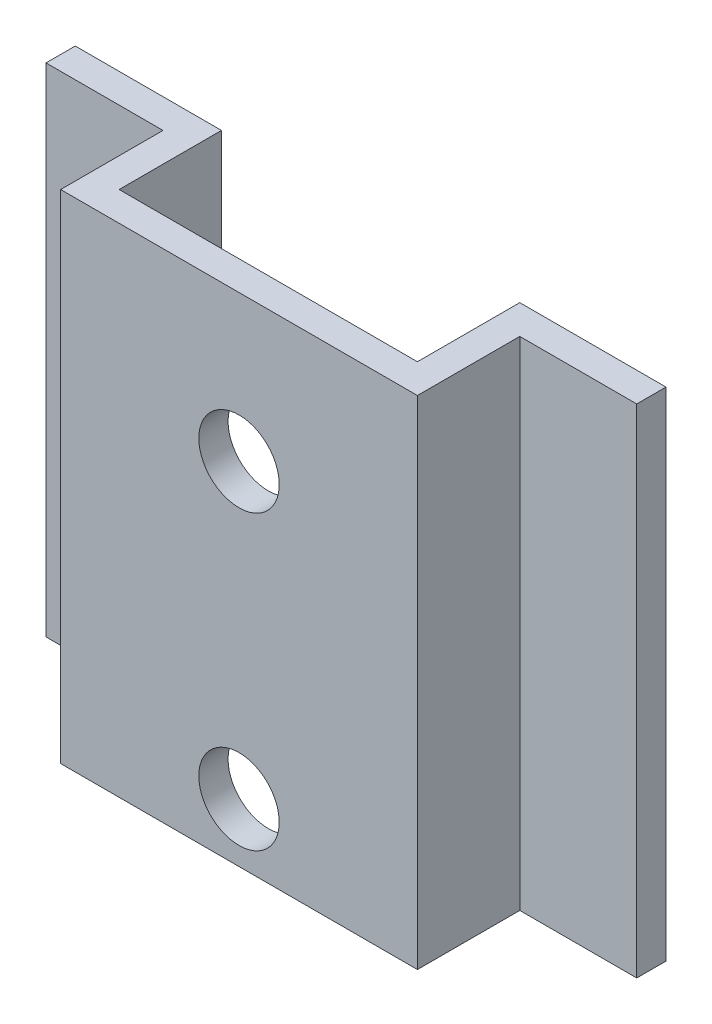
SolidWorks part; units mm, degrees
ref_plane "Front Plane" through (0, 0, 0) normal (0, 0, 1) x (1, 0, 0)
ref_plane "Top Plane" through (0, 0, 0) normal (0, 1, 0) x (1, 0, 0)
ref_plane "Right Plane" through (0, 0, 0) normal (1, 0, 0) x (0, 0, -1)
sketch "Sketch1" plane through (0, 0, 0) normal (0, 0, 1) x (1, 0, 0)
  line L1 (-10, 28) -> (10, 28)
  line L4 (-10, 27) -> (10, 27)
  line L5 (10, 27) -> (10, 62)
  line L6 (10, 62) -> (-10, 62)
  line L7 (-10, 62) -> (-10, 27)
  line L9 (10, 28) -> (10, 62)
  line L10 (10, 62) -> (-10, 62)
  line L11 (-10, 62) -> (-10, 28)
  circle A0 centre (0, 32) radius 2.75 construction
  circle A1 centre (0, 52) radius 2.75 construction
  circle A2 centre (0, 32) radius 2.75
  circle A3 centre (0, 52) radius 2.75
  dimension "D2" = 1
  dimension "D1" = 0
extrude "Boss-Extrude1" add sketch "Sketch1" along normal blind 2
sketch "Sketch2" plane through (0, 0, 0) normal (0, 0, -1) x (-1, 0, 0)
  line L0 (10, 62) -> (10.2, 62)
  line L1 (-10, 62) -> (-10.2, 62)
  line L2 (-10.2, 62) -> (-10.2, 28)
  line L3 (-10, 28) -> (-10.2, 28)
  line L4 (-10, 28) -> (-10, 62) construction
  line L5 (-10, 28) -> (-10, 62)
  line L6 (10.2, 62) -> (10.2, 28)
  line L7 (10, 28) -> (10.2, 28)
  line L8 (10, 62) -> (10, 28) construction
  line L9 (10, 62) -> (10, 28)
  line L11 (10.2, 62) -> (20.2, 62)
  line L12 (10.2, 62) -> (10.2, 28)
  line L13 (10.2, 28) -> (20.2, 28)
  line L14 (20.2, 62) -> (20.2, 28)
  line L15 (-10.2, 62) -> (-20.2, 62)
  line L16 (-10.2, 62) -> (-10.2, 28)
  line L17 (-10.2, 28) -> (-20.2, 28)
  line L18 (-20.2, 62) -> (-20.2, 28)
  dimension "D1" = 0.2
  dimension "D2" = 0.2
  dimension "D3" = 10
  dimension "D4" = 10
extrude "Boss-Extrude2" add sketch "Sketch2" against normal blind 2 separate body contours L14 L11 L6 L13 | L15 L18 L17 L2
sketch "Sketch3" plane through (0, 0, 0) normal (0, 0, -1) x (-1, 0, 0)
  line L4 (-10.2, 62) -> (-20.2, 62)
  line L5 (-20.2, 62) -> (-20.2, 28)
  line L6 (-20.2, 28) -> (-10.2, 28)
  line L7 (-10.2, 28) -> (-10.2, 62)
  line L8 (-10.2, 62) -> (-20.2, 62)
  line L9 (-20.2, 62) -> (-20.2, 28)
  line L10 (-20.2, 28) -> (-10.2, 28)
  line L11 (-10.2, 28) -> (-10.2, 62)
  line L12 (20.2, 28) -> (20.2, 62)
  line L13 (20.2, 62) -> (10.2, 62)
  line L14 (10.2, 62) -> (10.2, 28)
  line L15 (10.2, 28) -> (20.2, 28)
  line L16 (20.2, 28) -> (20.2, 62)
  line L17 (20.2, 62) -> (10.2, 62)
  line L18 (10.2, 62) -> (10.2, 28)
  line L19 (10.2, 28) -> (20.2, 28)
  dimension "D1" = 0
  dimension "D2" = 0
extrude "Boss-Extrude3" add sketch "Sketch3" along normal up to surface (7 mm away)
sketch "Sketch4" plane through (0, 62, 0) normal (0, 1, 0) x (1, 0, 0)
  line L0 (-10.2, -2) -> (-10.2, 7) construction
  line L1 (10.2, -2) -> (-10.2, -2)
  line L2 (10.2, -2) -> (10.2, 0)
  line L3 (10.2, 0) -> (-10.2, 0)
  line L4 (-10.2, -2) -> (-10.2, 0)
extrude "Boss-Extrude4" add sketch "Sketch4" against normal up to surface (34 mm away) up to face at (-15.2, 28, -2.5)
sketch "Sketch5" plane through (0, 62, 0) normal (0, 1, 0) x (1, 0, 0)
  line L0 (10.2, 0) -> (12.2, 0)
  line L1 (-10.2, 0) -> (-12.2, 0)
  line L2 (-12.2, 0) -> (-12.2, -2)
  line L3 (20.2, -2) -> (-20.2, -2) construction
  line L4 (12.2, 0) -> (12.2, -2)
  line L5 (-20.2, 7) -> (-20.2, 5)
  line L6 (-20.2, -2) -> (-20.2, 7) construction
  line L7 (20.2, 7) -> (20.2, 5)
  line L8 (20.2, -2) -> (20.2, 7) construction
  line L10 (20.2, 5) -> (12.2, 5)
  line L11 (20.2, 5) -> (20.2, -2)
  line L12 (20.2, -2) -> (12.2, -2)
  line L13 (12.2, 5) -> (12.2, -2)
  line L14 (-12.2, -2) -> (-20.2, -2)
  line L15 (-12.2, -2) -> (-12.2, 5)
  line L16 (-12.2, 5) -> (-20.2, 5)
  line L17 (-20.2, -2) -> (-20.2, 5)
  line M8 (-20.2, 7) -> (-20.2, -2)
  line M9 (-20.2, -2) -> (20.2, -2)
  line M10 (20.2, -2) -> (20.2, 7)
  dimension "D1" = 2
  dimension "D2" = 2
  dimension "D3" = 2
  dimension "D4" = 2
extrude "Cut-Extrude2" cut sketch "Sketch5" against normal through all contours L10 L13 L4 M9 M10 | L15 L16 L2 M8 M9
sketch "Sketch6" plane through (0, 0, 0) normal (0, 0, -1) x (-1, 0, 0)
  circle A0 centre (0, 52) radius 2.75
  circle A1 centre (0, 32) radius 2.75
extrude "Cut-Extrude3" cut sketch "Sketch6" against normal through all
